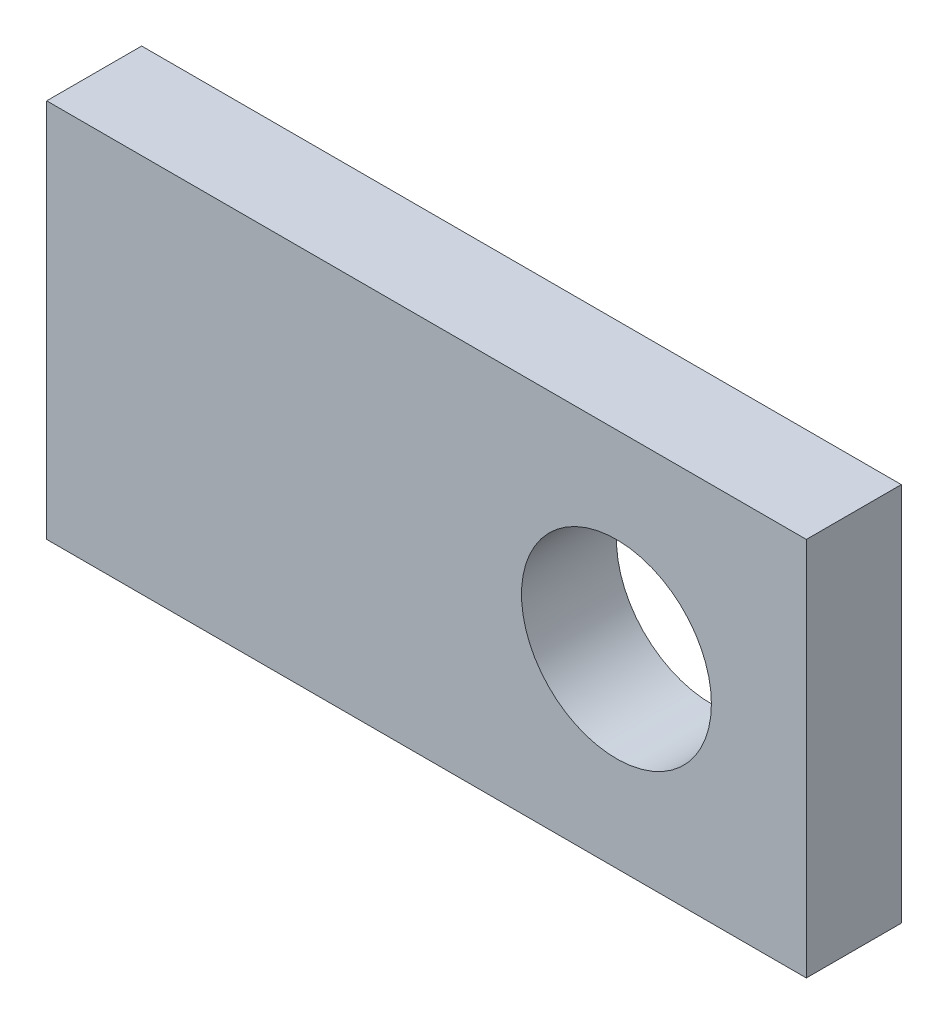
SolidWorks part; units mm, degrees
ref_plane "Alzado" through (0, 0, 0) normal (0, 0, 1) x (1, 0, 0)
ref_plane "Planta" through (0, 0, 0) normal (0, 1, 0) x (1, 0, 0)
ref_plane "Vista lateral" through (0, 0, 0) normal (1, 0, 0) x (0, 0, -1)
sketch "Croquis1" plane through (0, 0, 0) normal (0, 0, 1) x (1, 0, 0)
  line L1 (0, 0) -> (50.8, 0)
  line L2 (0, 0) -> (0, 25.4)
  line L3 (0, 25.4) -> (50.8, 25.4)
  line L4 (50.8, 0) -> (50.8, 25.4)
  circle A0 centre (38.1, 12.7) radius 6.35
  dimension "D3" = 12.7
  dimension "D4" = 38.1
  dimension "D5" = 12.7
  dimension "D1" = 25.4
  dimension "D2" = 50.8
extrude "Saliente-Extruir1" add sketch "Croquis1" along normal blind 6.35
